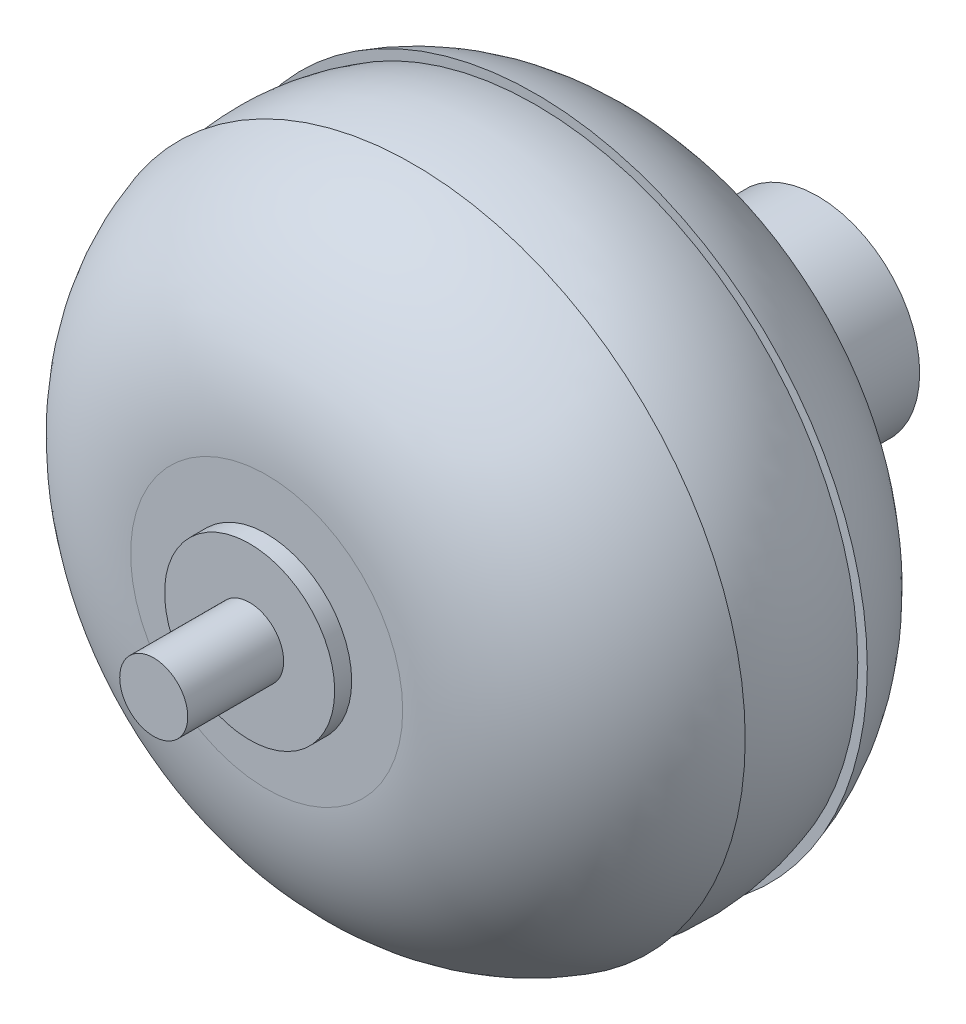
SolidWorks part; units mm, degrees
ref_plane "Front Plane" through (0, 0, 0) normal (0, 0, 1) x (1, 0, 0)
ref_plane "Top Plane" through (0, 0, 0) normal (0, 1, 0) x (1, 0, 0)
ref_plane "Right Plane" through (0, 0, 0) normal (1, 0, 0) x (0, 0, -1)
sketch "Sketch1" plane through (0, 0, 0) normal (0, 0, 1) x (1, 0, 0)
  circle A0 centre (0, 0) radius 10
extrude "Boss-Extrude1" add sketch "Sketch1" along normal blind 12.2
sketch "Sketch4" plane through (0, 0, 12.2) normal (0, 0, 1) x (1, 0, 0)
  circle A0 centre (0, 0) radius 2.5
extrude "Boss-Extrude3" add sketch "Sketch4" along normal blind 0.5
sketch "Sketch5" plane through (0, 0, 12.2) normal (0, 0, 1) x (1, 0, 0)
  circle A0 centre (0, 0) radius 1
extrude "Boss-Extrude4" add sketch "Sketch5" along normal blind 3.32
fillet "Fillet1" radius 6 2 edges at (10, 0, 12.2) (10, 0, 0)
sketch "Sketch2" plane through (0, 0, 0) normal (0, 0, -1) x (-1, 0, 0)
  circle A0 centre (0, 0) radius 3
  dimension "D1" = 6
extrude "Boss-Extrude2" add sketch "Sketch2" along normal blind 4
sketch "Sketch6" plane through (0, 0, -4) normal (0, 0, -1) x (-1, 0, 0)
  circle A0 centre (0, 0) radius 2.02
  dimension "D1" = 4.04
extrude "Cut-Extrude1" cut sketch "Sketch6" against normal blind 2.5
sketch "Sketch7" plane through (0, 0, 0) normal (1, 0, 0) x (0, 0, -1)
  line L0 (-15.1934, 0) -> (8.0917, 0) construction
  line L1 (-7.8873, 10.5991) -> (-4.2911, 10.5991)
  line L2 (-7.8873, 10.5991) -> (-7.8873, 9.4712)
  line L4 (-4.2911, 10.5991) -> (-4.2911, 9.4712)
  arc A0 (-7.8873, 9.4712) -> (-4.2911, 9.4712) centre (-6.0892, 3.9749) cw
  dimension "D1" = 3.5962
revolve "Cut-Revolve1" cut sketch "Sketch7" angle 360 about L0
